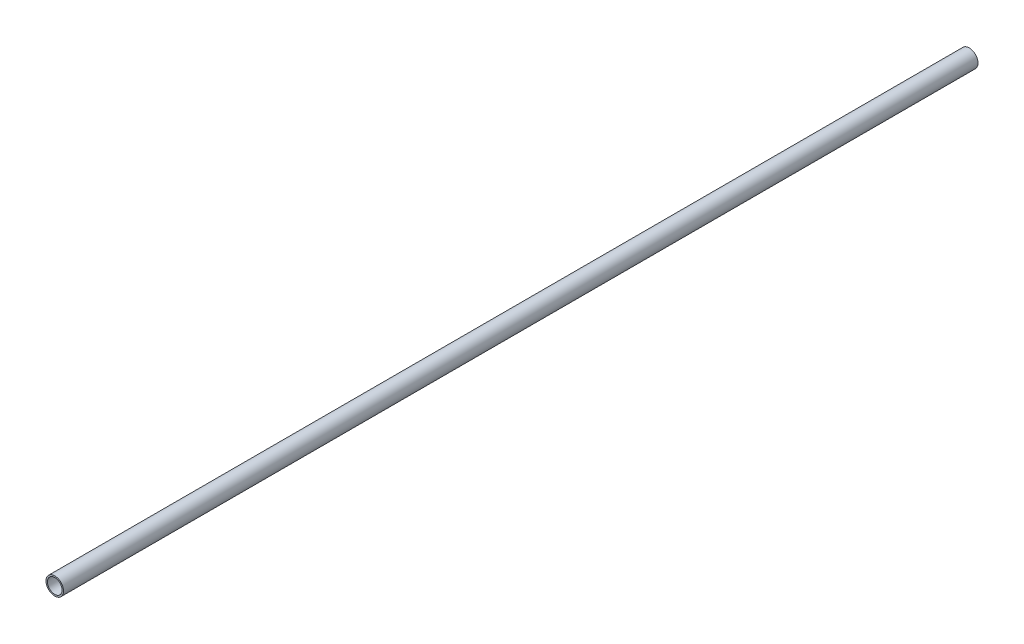
SolidWorks part; units mm, degrees
material "AISI SS316"
ref_plane "Front" through (0, 0, 0) normal (0, 0, 1) x (1, 0, 0)
ref_plane "Top" through (0, 0, 0) normal (0, 1, 0) x (1, 0, 0)
ref_plane "Right" through (0, 0, 0) normal (1, 0, 0) x (0, 0, -1)
sketch "Sketch1" plane through (0, 0, 0) normal (0, 0, 1) x (1, 0, 0)
  circle A0 centre (0, 0) radius 6
  circle A1 centre (0, 0) radius 5
  dimension "D1" = 12
  dimension "D2" = 1
extrude "Extrude1" add sketch "Sketch1" along normal mid plane 625
